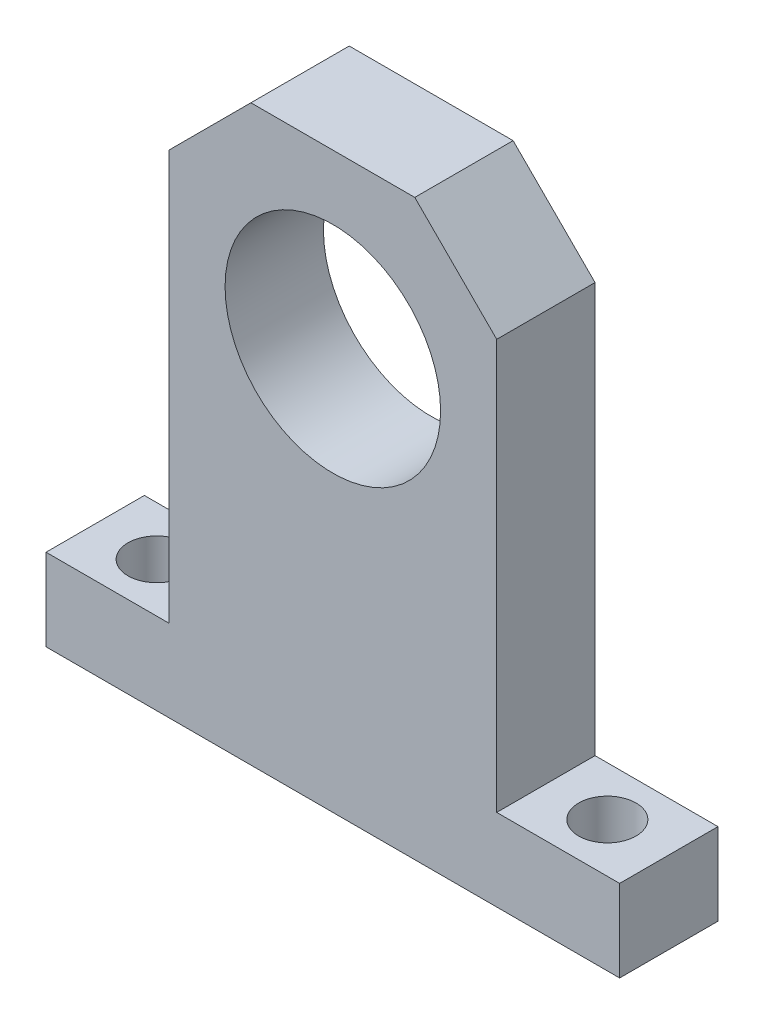
SolidWorks part; units mm, degrees
ref_plane "前基準面" through (0, 0, 0) normal (0, 0, 1) x (1, 0, 0)
ref_plane "上基準面" through (0, 0, 0) normal (0, 1, 0) x (1, 0, 0)
ref_plane "右基準面" through (0, 0, 0) normal (1, 0, 0) x (0, 0, -1)
sketch "草圖1" plane through (0, 0, 0) normal (0, 0, 1) x (1, 0, 0)
  line L0 (40, 0) -> (55, 0)
  line L2 (0, 0) -> (0, 60)
  line L3 (0, 60) -> (40, 60)
  line L4 (40, 0) -> (40, 60)
  line L5 (-15, 0) -> (0, 0)
  line L6 (-15, 0) -> (-15, -10)
  line L7 (-15, -10) -> (55, -10)
  line L8 (55, 0) -> (55, -10)
  circle A0 centre (20, 39) radius 13.15
  point P11 (20, 60)
  point P12 (20, -10)
  dimension "D1" = 26.3
  dimension "D2" = 49
  dimension "D3" = 10
  dimension "D4" = 60
  dimension "D5" = 40
  dimension "D6" = 15
extrude "填料-伸長1" add sketch "草圖1" along normal blind 12 contours A0 | L2 L3 L4 L0 L8 L7 L6 L5
sketch "草圖2" plane through (0, 0, 0) normal (0, 1, 0) x (1, 0, 0)
  line L0 (40, -12) -> (55, -12) construction
  line L1 (55, -12) -> (55, 0) construction
  circle A0 centre (47.5, -6) radius 3.5
  point P5 (47.5, -12)
  point P9 (55, -6)
  dimension "D1" = 7
extrude "除料-伸長2" cut sketch "草圖2" against normal through all contours A0
sketch "草圖3" plane through (0, 0, 0) normal (0, 1, 0) x (1, 0, 0)
  line L0 (-15, -12) -> (-15, 0) construction
  line L1 (-15, 0) -> (0, 0) construction
  circle A0 centre (-7.5, -6) radius 3.5
  point P5 (-15, -6)
  point P8 (-7.5, 0)
  dimension "D1" = 7
extrude "除料-伸長3" cut sketch "草圖3" against normal through all
chamfer "導角1" distance 10 angle 45 1 edges at (0, 60, 6)
chamfer "導角2" distance 10 angle 45 1 edges at (40, 60, 6)
